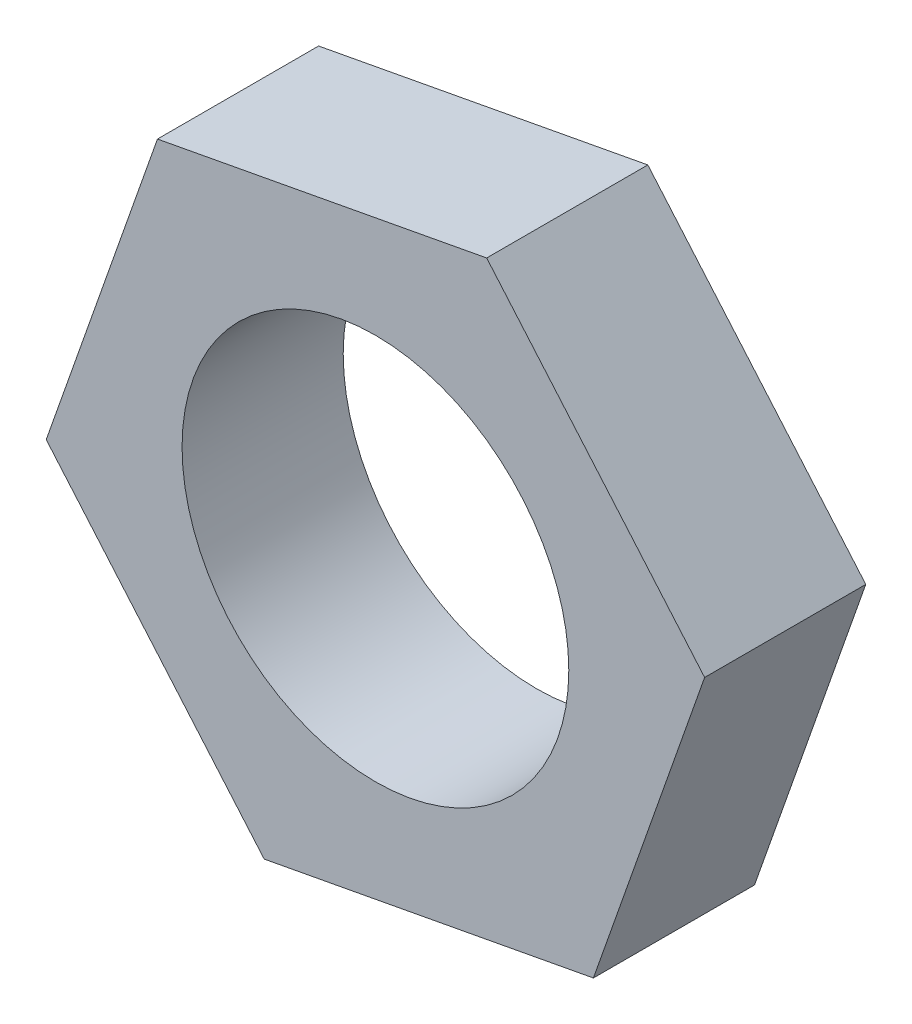
SolidWorks part; units mm, degrees
material "AISI 304"
ref_plane "Front Plane" through (0, 0, 0) normal (0, 0, 1) x (1, 0, 0)
ref_plane "Top Plane" through (0, 0, 0) normal (0, 1, 0) x (1, 0, 0)
ref_plane "Right Plane" through (0, 0, 0) normal (1, 0, 0) x (0, 0, -1)
sketch "Sketch1" plane through (0, 0, 0) normal (0, 0, 1) x (1, 0, 0)
  line L1 (6.7632, -7.8904) -> (10.2149, 1.9119)
  line L2 (10.2149, 1.9119) -> (3.4517, 9.8023)
  line L3 (3.4517, 9.8023) -> (-6.7632, 7.8904)
  line L4 (-6.7632, 7.8904) -> (-10.2149, -1.9119)
  line L5 (-10.2149, -1.9119) -> (-3.4517, -9.8023)
  line L6 (-3.4517, -9.8023) -> (6.7632, -7.8904)
  circle A0 centre (0, 0) radius 9 construction
  circle A1 centre (0, 0) radius 6
  dimension "D1" = 18
  dimension "D2" = 12
extrude "Boss-Extrude1" add sketch "Sketch1" along normal mid plane 5
